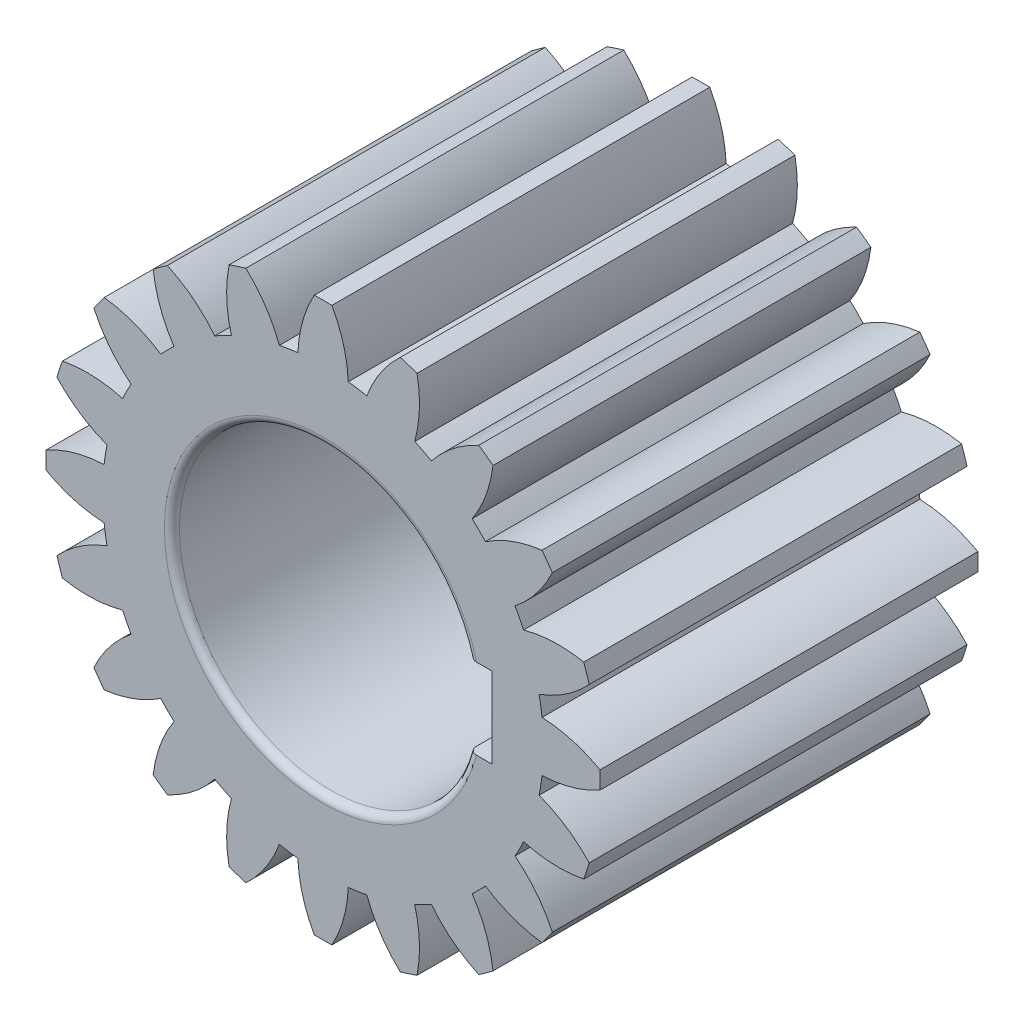
SolidWorks part; units mm, degrees
ref_plane "前视" through (0, 0, 0) normal (0, 0, 1) x (1, 0, 0)
ref_plane "上视" through (0, 0, 0) normal (0, 1, 0) x (1, 0, 0)
ref_plane "右视" through (0, 0, 0) normal (1, 0, 0) x (0, 0, -1)
sketch "草图1" plane through (0, 0, 0) normal (0, 0, 1) x (1, 0, 0)
  circle A0 centre (0, 0) radius 87.5
  dimension "D1" = 175
extrude "拉伸1" add sketch "草图1" along normal blind 150
sketch "草图2" plane through (0, 0, 0) normal (0, 0, 1) x (1, 0, 0)
  line L0 (0, 0) -> (0, 131.4756) construction
  line L1 (0, 0) -> (-10.368, 131.7378) construction
  line L2 (-3.5, 131.4756) -> (-3.5, 84.1531) construction
  line L3 (-10, 131.7378) -> (-10, 81.3397) construction
  circle A0 centre (0, 0) radius 87.5 construction
  arc A1 (10, 86.9267) -> (-10, 86.9267) centre (0, 0) ccw
  circle A2 centre (0, 0) radius 100 construction
  arc A3 (3.5, 109.9443) -> (-3.5, 109.9443) centre (0, 0) ccw
  arc A4 (-3.5, 109.9443) -> (-10, 86.9267) centre (41.5852, 84.786) ccw
  arc A5 (3.5, 109.9443) -> (10, 86.9267) centre (-41.5852, 84.786) cw
  point P8 (-7.8459, 99.6917)
  dimension "D1" = 200
  dimension "D2" = 220
  dimension "D3" = 4.5
  dimension "D4" = 3.5
  dimension "D5" = 10
extrude "拉伸2" add sketch "草图2" along normal blind 150
pattern_circular "阵列(圆周)1" count 20 over 360 about axis through (0, 0, 0) along (0, 0, 1) of "拉伸2"
sketch "草图3" plane through (0, 0, 0) normal (0, 0, 1) x (1, 0, 0)
  line L1 (57.8273, 16) -> (67, 16)
  line L3 (57.8273, -16) -> (67, -16)
  line L4 (67, 16) -> (67, -16)
  arc A0 (57.8273, 16) -> (57.8273, -16) centre (0, 0) ccw
  dimension "D1" = 120
  dimension "D2" = 67
  dimension "D3" = 32
  dimension "D4" = 16
extrude "切除-拉伸1" cut sketch "草图3" along normal through all
fillet "圆角1" radius 3 2 edges at (-60, 0, 0) (-60, 0, 150)
